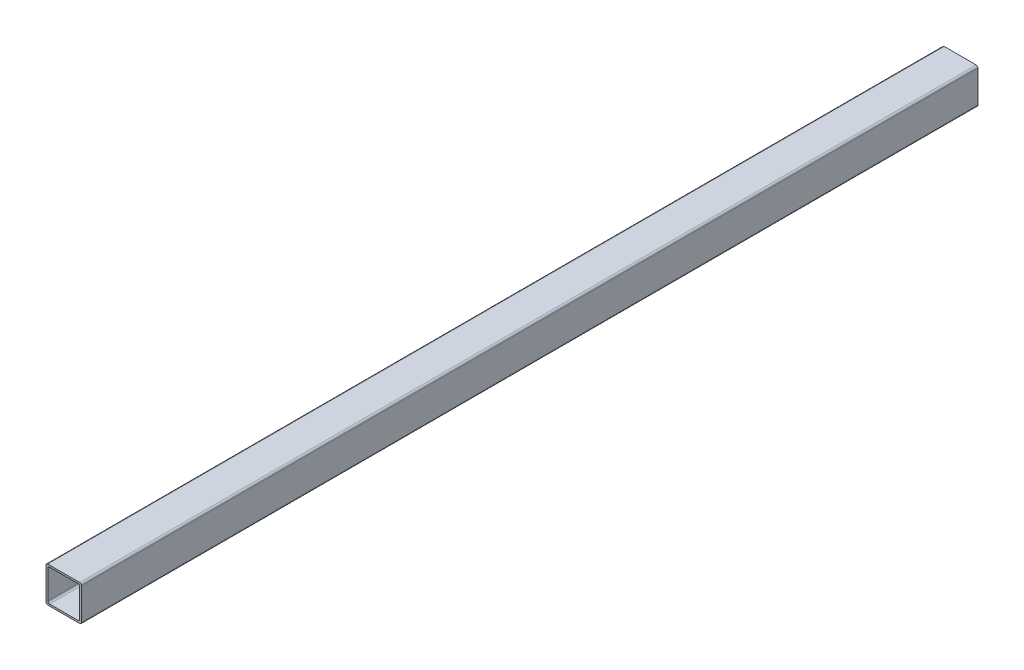
SolidWorks part; units mm, degrees
ref_plane "Спереди" through (0, 0, 0) normal (0, 0, 1) x (1, 0, 0)
ref_plane "Сверху" through (0, 0, 0) normal (0, 1, 0) x (1, 0, 0)
ref_plane "Справа" through (0, 0, 0) normal (1, 0, 0) x (0, 0, -1)
sketch "Эскиз1" plane through (0, 0, 0) normal (0, 0, 1) x (1, 0, 0)
  line L1 (-16, 18) -> (16, 18)
  line L2 (-18, 16) -> (-18, -16)
  line L3 (-16, -18) -> (16, -18)
  line L4 (18, 16) -> (18, -16)
  line L5 (-18, 18) -> (18, -18) construction
  line L6 (-18, -18) -> (18, 18) construction
  line L7 (18, -20) -> (-18, -20)
  line L8 (20, -18) -> (20, 18)
  line L9 (18, 20) -> (-18, 20)
  line L10 (-20, -18) -> (-20, 18)
  line L11 (20, -20) -> (-20, 20) construction
  line L12 (20, 20) -> (-20, -20) construction
  arc A0 (20, 18) -> (18, 20) centre (18, 18) ccw
  arc A1 (16, 18) -> (18, 16) centre (16, 16) cw
  arc A2 (18, -20) -> (20, -18) centre (18, -18) ccw
  arc A3 (16, -18) -> (18, -16) centre (16, -16) ccw
  arc A4 (-18, -20) -> (-20, -18) centre (-18, -18) cw
  arc A5 (-18, -16) -> (-16, -18) centre (-16, -16) ccw
  arc A6 (-16, 18) -> (-18, 16) centre (-16, 16) ccw
  arc A7 (-18, 20) -> (-20, 18) centre (-18, 18) ccw
  point P0 (0, 0)
  point P6 (0, 0)
  dimension "D5" = 2
  dimension "D1" = 40
  dimension "D2" = 40
  dimension "D3" = 2
  dimension "D4" = 2
extrude "Бобышка-Вытянуть1" add sketch "Эскиз1" along normal blind 1010
